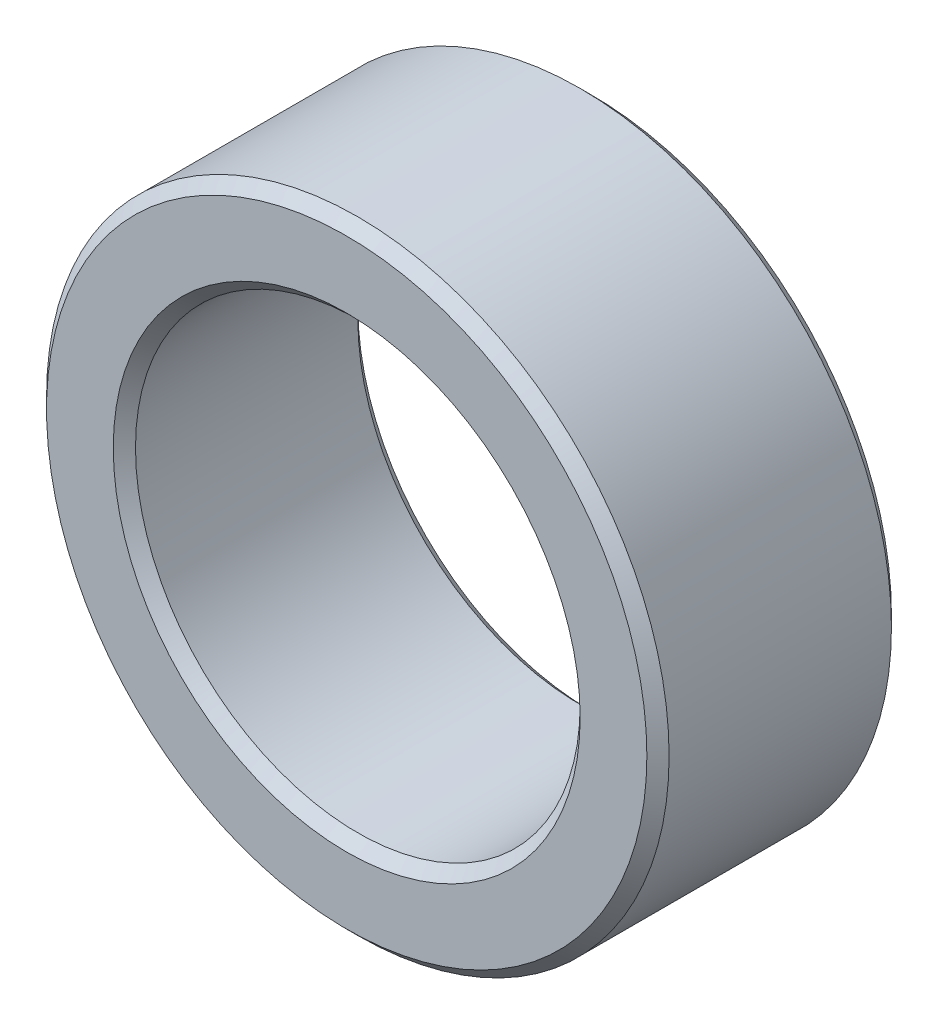
SolidWorks part; units mm, degrees
material "AISI 4130 Steel, normalized at 870C"
ref_plane "Front Plane" through (0, 0, 0) normal (0, 0, 1) x (1, 0, 0)
ref_plane "Top Plane" through (0, 0, 0) normal (0, 1, 0) x (1, 0, 0)
ref_plane "Right Plane" through (0, 0, 0) normal (1, 0, 0) x (0, 0, -1)
sketch "BK Collar Sketch" plane through (0, 0, 0) normal (0, 0, 1) x (1, 0, 0)
  circle A0 centre (0, 0) radius 7
  circle A1 centre (0, 0) radius 5
  dimension "DO" = 14
  dimension "d1" = 10
extrude "BK Collar" add sketch "BK Collar Sketch" along normal blind 5.5
chamfer "BK Collar Chamfer" distance 0.25 angle 45 4 edges at (5, 0, 0) (7, 0, 0) (5, 0, 5.5) (7, 0, 5.5)
